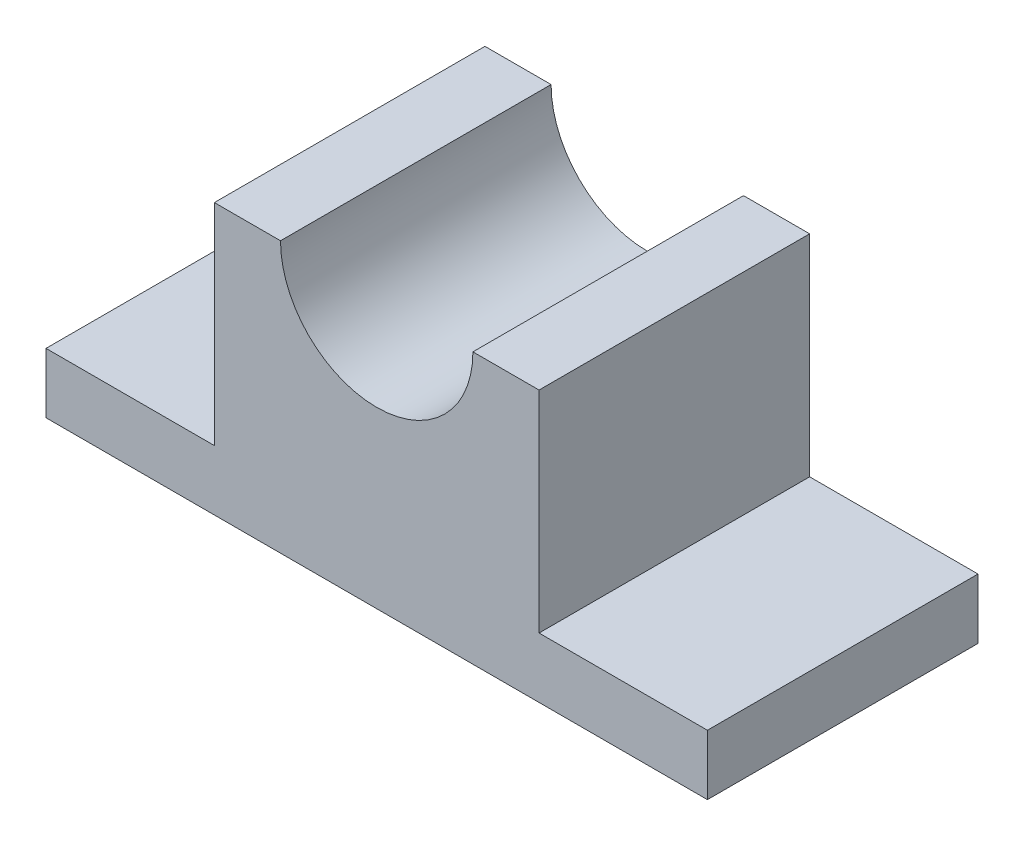
SolidWorks part; units mm, degrees
ref_plane "정면" through (0, 0, 0) normal (0, 0, 1) x (1, 0, 0)
ref_plane "윗면" through (0, 0, 0) normal (0, 1, 0) x (1, 0, 0)
ref_plane "우측면" through (0, 0, 0) normal (1, 0, 0) x (0, 0, -1)
sketch "스케치1" plane through (0, 0, 0) normal (0, 0, 1) x (1, 0, 0)
  line L0 (-55, 0) -> (55, 0)
  line L1 (55, 0) -> (55, 10)
  line L2 (55, 10) -> (27, 10)
  line L3 (27, 10) -> (27, 45)
  line L4 (27, 45) -> (-27, 45)
  line L5 (-27, 45) -> (-27, 10)
  line L6 (-27, 10) -> (-55, 10)
  line L7 (-55, 10) -> (-55, 0)
  dimension "D1" = 110
  dimension "D2" = 54
  dimension "D3" = 10
  dimension "D4" = 45
  dimension "D5" = 55
extrude "보스-돌출1" add sketch "스케치1" along normal blind 45
sketch "스케치2" plane through (0, 0, 0) normal (0, 0, -1) x (-1, 0, 0)
  line L0 (-27, 45) -> (27, 45) construction
  circle A0 centre (0, 45) radius 16
  dimension "D1" = 32
extrude "컷-돌출1" cut sketch "스케치2" against normal through all
sketch "스케치3" plane through (0, 0, 0) normal (0, 0, -1) x (-1, 0, 0)
  circle A0 centre (0, 45) radius 19
  dimension "D1" = 38
